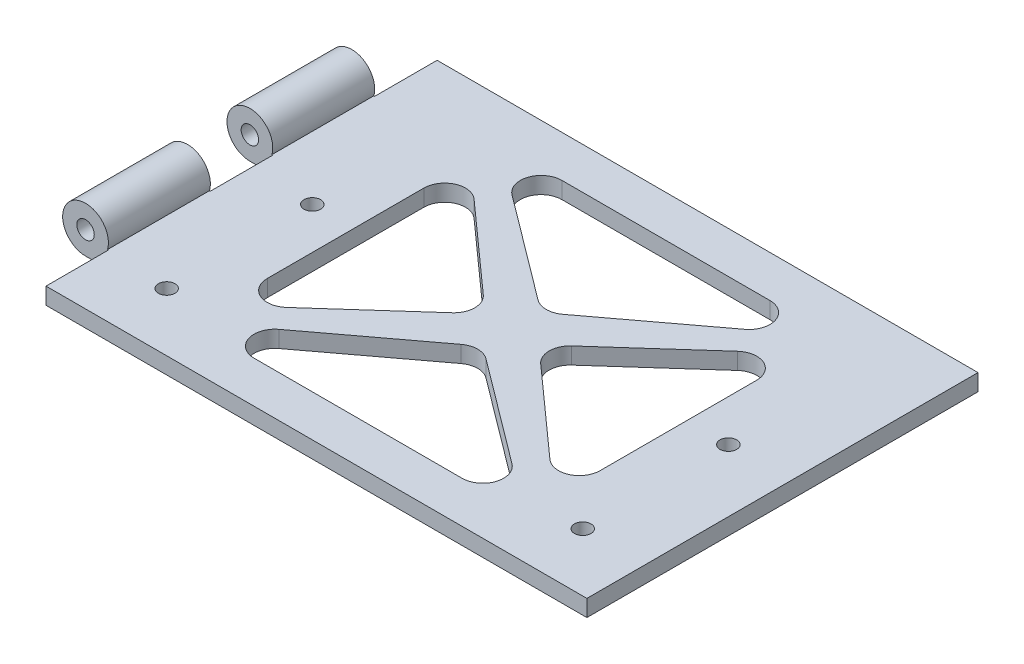
SolidWorks part; units mm, degrees
ref_plane "Front" through (0, 0, 0) normal (0, 0, 1) x (1, 0, 0)
ref_plane "Top" through (0, 0, 0) normal (0, 1, 0) x (1, 0, 0)
ref_plane "Right" through (0, 0, 0) normal (1, 0, 0) x (0, 0, -1)
sketch "Эскиз1" plane through (0, 0, 0) normal (0, 1, 0) x (1, 0, 0)
  line L0 (-56.7404, 0) -> (-93.3445, 0) construction
  line L1 (-65, 47) -> (65, 47)
  line L2 (-65, 47) -> (-65, -47)
  line L3 (-65, -47) -> (65, -47)
  line L4 (65, 47) -> (65, -47)
  line L5 (-65, 47) -> (65, -47) construction
  line L6 (-65, -47) -> (65, 47) construction
  point P0 (0, 0)
  dimension "D1" = 130
  dimension "D2" = 94
extrude "Бобышка-Вытянуть1" add sketch "Эскиз1" along normal blind 4
sketch "Эскиз2" plane through (0, 0, 0) normal (0, 0, 1) x (1, 0, 0)
  line L1 (-65, 4) -> (-65.2085, 4)
  line L2 (-65, 0) -> (65, 0) construction
  line L3 (-65, 4) -> (-65, 0)
  line L4 (-65, 0) -> (-70.5, 0)
  arc A0 (-65.2085, 4) -> (-70.5, 0) centre (-70.5, 5.5) ccw
  dimension "D1" = 11
extrude "Бобышка-Вытянуть2" add sketch "Эскиз2" along normal blind 32 and the other way blind 32
sketch "Эскиз4" plane through (0, 0, 47) normal (0, 0, 1) x (1, 0, 0)
  circle A0 centre (-70.5, 5.5) radius 2.1
  dimension "D1" = 4.2
extrude "Вырез-Вытянуть1" cut sketch "Эскиз4" against normal through all
sketch "Эскиз10" plane through (0, 0, 0) normal (0, 1, 0) x (1, 0, 0)
  line L0 (-88.6964, 0) -> (-22.4603, 0) construction
  line L1 (-70.5, 37.7116) -> (-70.5, -44.793) construction
  line L2 (-65, -32) -> (-65, 32) construction
  line L3 (-76, 7.5) -> (-65, 7.5)
  line L4 (-76, 7.5) -> (-76, -7.5)
  line L5 (-76, -7.5) -> (-65, -7.5)
  line L6 (-65, 7.5) -> (-65, -7.5)
  line L7 (-76, 7.5) -> (-65, -7.5) construction
  line L8 (-76, -7.5) -> (-65, 7.5) construction
  point P6 (-70.5, 0)
  dimension "D1" = 15
  dimension "D2" = 11
extrude "Вырез-Вытянуть2" cut sketch "Эскиз10" along normal blind 24
sketch "Эскиз11" plane through (0, 4, 0) normal (0, 1, 0) x (1, 0, 0)
  line L0 (-25, 37) -> (25, 37)
  line L1 (28, 28) -> (3, 9.25)
  line L2 (-3, 9.25) -> (-28, 28)
  line L3 (-3, -9.25) -> (-28, -28)
  line L4 (-25, -37) -> (25, -37)
  line L5 (28, -28) -> (3, -9.25)
  line L6 (-10.6256, 3.7268) -> (-31.6667, 22.5464)
  line L7 (-40, 18.8197) -> (-40, -18.8197)
  line L8 (-31.6667, -22.5464) -> (-10.6256, -3.7268)
  line L9 (10.6256, 3.7268) -> (31.6667, 22.5464)
  line L10 (40, 18.8197) -> (40, -18.8197)
  line L11 (31.6667, -22.5464) -> (10.6256, -3.7268)
  line L12 (65, 47) -> (-65, 47) construction
  line L13 (-65, -47) -> (65, -47) construction
  line L14 (65, -47) -> (65, 47) construction
  line L15 (-65, 47) -> (-65, 32) construction
  arc A0 (-3, -9.25) -> (3, -9.25) centre (0, -13.25) cw
  arc A1 (3, 9.25) -> (-3, 9.25) centre (0, 13.25) cw
  arc A2 (-10.6256, 3.7268) -> (-10.6256, -3.7268) centre (-13.959, 0) cw
  arc A3 (10.6256, 3.7268) -> (10.6256, -3.7268) centre (13.959, 0) ccw
  arc A4 (40, -18.8197) -> (31.6667, -22.5464) centre (35, -18.8197) cw
  arc A5 (31.6667, 22.5464) -> (40, 18.8197) centre (35, 18.8197) cw
  arc A6 (-40, -18.8197) -> (-31.6667, -22.5464) centre (-35, -18.8197) ccw
  arc A7 (-31.6667, 22.5464) -> (-40, 18.8197) centre (-35, 18.8197) ccw
  arc A8 (25, -37) -> (28, -28) centre (25, -32) ccw
  arc A9 (-28, -28) -> (-25, -37) centre (-25, -32) ccw
  arc A10 (25, 37) -> (28, 28) centre (25, 32) cw
  arc A11 (-25, 37) -> (-28, 28) centre (-25, 32) ccw
  point P11 (0, -37)
  point P13 (0, 0)
  point P14 (0, 0)
  point P17 (0, -47)
  point P25 (0, 0)
  point P28 (0, -7)
  point P31 (0, 7)
  point P34 (-6.459, 0)
  point P37 (6.459, 0)
  point P40 (40, -30)
  point P43 (40, 30)
  point P46 (-40, -30)
  point P49 (-40, 30)
  point P52 (40, -37)
  point P55 (-40, -37)
  point P58 (40, 37)
  point P61 (-40, 37)
  dimension "D14" = 5
  dimension "D1" = 80
  dimension "D2" = 50
  dimension "D3" = 50
  dimension "D4" = 60
  dimension "D5" = 45
  dimension "D6" = 45
  dimension "D7" = 60
  dimension "D8" = 45
  dimension "D9" = 45
  dimension "D10" = 10
  dimension "D11" = 10
  dimension "D12" = 25
  dimension "D13" = 25
extrude "Вырез-Вытянуть3" cut sketch "Эскиз11" against normal blind 10
sketch "Эскиз12" plane through (0, 4, 0) normal (0, 1, 0) x (1, 0, 0)
  line L0 (65, 47) -> (-65, 47) construction
  line L1 (-65, 47) -> (-65, 32) construction
  line L2 (65, -47) -> (65, 47) construction
  line L4 (-65, -32) -> (-65, -47) construction
  circle A0 centre (-50, 2) radius 2
  circle A1 centre (50, 2) radius 2
  circle A2 centre (50, -33) radius 2
  circle A3 centre (-50, -33) radius 2
  dimension "D1" = 4
  dimension "D2" = 45
  dimension "D3" = 15
  dimension "D6" = 15
  dimension "D7" = 45
  dimension "D9" = 15
  dimension "D4" = 2
  dimension "D5" = 2
extrude "Вырез-Вытянуть4" cut sketch "Эскиз12" against normal blind 10
